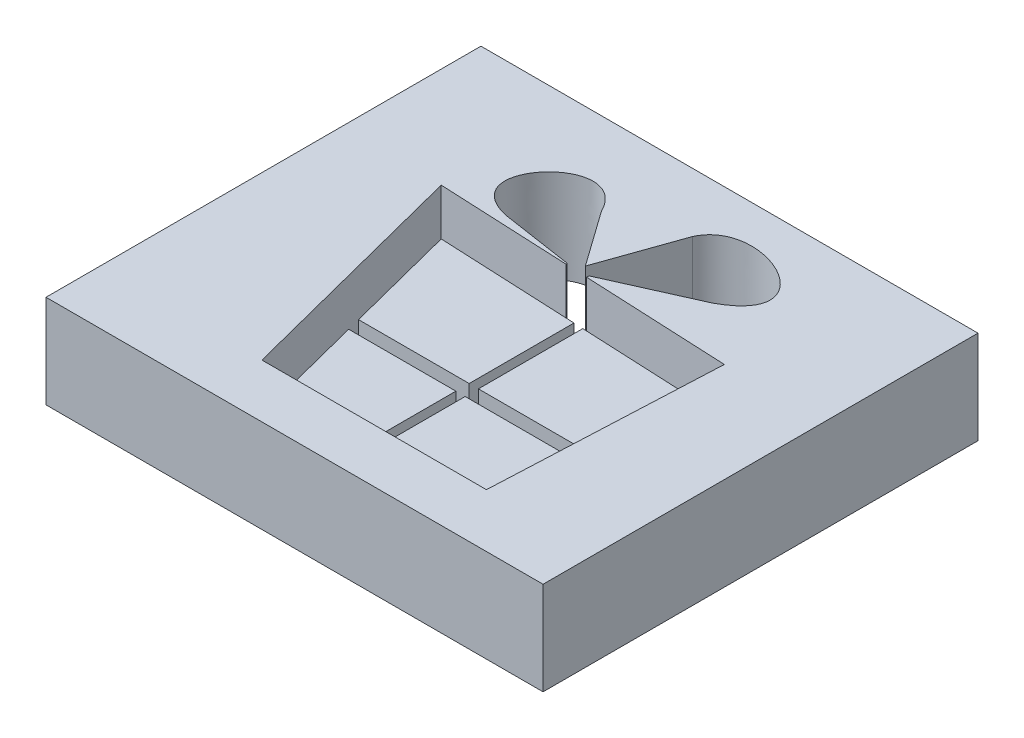
SolidWorks part; units mm, degrees
ref_plane "Front Plane" through (0, 0, 0) normal (0, 0, 1) x (1, 0, 0)
ref_plane "Top Plane" through (0, 0, 0) normal (0, 1, 0) x (1, 0, 0)
ref_plane "Right Plane" through (0, 0, 0) normal (1, 0, 0) x (0, 0, -1)
sketch "Sketch1" plane through (0, 0, 0) normal (0, 1, 0) x (1, 0, 0)
  line L1 (-42.8025, 22.3185) -> (-26.8025, 22.3185)
  line L2 (-42.8025, 22.3185) -> (-42.8025, 8.3185)
  line L3 (-42.8025, 8.3185) -> (-26.8025, 8.3185)
  line L4 (-26.8025, 22.3185) -> (-26.8025, 8.3185)
  dimension "D1" = 16
  dimension "D2" = 14
extrude "Boss-Extrude1" add sketch "Sketch1" along normal blind 3
sketch "Sketch2" plane through (0, 3, 0) normal (0, 1, 0) x (1, 0, 0)
  line L0 (-39.5675, 17.8055) -> (-35.0877, 17.598)
  line L1 (-30.0115, 17.3629) -> (-30.3506, 10.0431)
  line L2 (-30.3506, 10.0431) -> (-37.5756, 10.0431)
  line L3 (-37.5756, 10.0431) -> (-39.5675, 17.8055)
  line L4 (-35.0877, 17.598) -> (-35.0877, 14.2249)
  line L5 (-35.0877, 14.2249) -> (-38.6487, 14.2249)
  line L7 (-38.5391, 13.7977) -> (-35.0883, 13.7977)
  line L8 (-35.0883, 13.7977) -> (-35.0883, 10.0431)
  line L10 (-34.7895, 10.0431) -> (-34.7895, 13.7977)
  line L11 (-34.7895, 13.7977) -> (-30.1767, 13.7977)
  line L13 (-30.1569, 14.2249) -> (-34.7895, 14.2249)
  line L14 (-34.7895, 14.2249) -> (-34.7895, 17.5842)
  line L19 (-34.0907, 20.4179) -> (-34.9919, 17.869)
  line L20 (-36.2576, 19.6502) -> (-34.9919, 17.869)
  line L21 (-37.6692, 18.0034) -> (-35.3618, 17.6542)
  line L22 (-35.3618, 17.6542) -> (-35.3618, 17.6107)
  line L23 (-31.9114, 18.8834) -> (-34.6581, 17.6542)
  line L24 (-34.6581, 17.6542) -> (-34.6581, 17.5781)
  line L25 (-34.7895, 17.5842) -> (-30.0115, 17.3629)
  spline S0 degree 3 poles (-31.9114, 18.8834) (-29.3743, 20.2485) (-33.3059, 22.1353) (-34.0907, 20.4179) knots 0 0 0 0 1 1 1 1
  spline S1 degree 3 poles (-36.2576, 19.6502) (-37.3045, 21.7599) (-40.1557, 18.5404) (-37.6692, 18.0034) knots 0 0 0 0 1 1 1 1
extrude "Cut-Extrude5" cut sketch "Sketch2" against normal blind 3 contours L20 S1 L21 L22 L0 L4 L5 L3 L7 L8 L2 L10 L11 L1 L13 L14 L25 L24 L23 S0 L19
sketch "Sketch3" plane through (0, 3, 0) normal (0, 1, 0) x (1, 0, 0)
  line L0 (-35.0877, 17.598) -> (-39.5675, 17.8055)
  line L1 (-39.5675, 17.8055) -> (-37.5756, 10.0431)
  line L2 (-37.5756, 10.0431) -> (-30.3506, 10.0431)
  line L3 (-30.3506, 10.0431) -> (-30.0115, 17.3629)
  line L4 (-30.0115, 17.3629) -> (-35.0877, 17.598)
extrude "Cut-Extrude6" cut sketch "Sketch3" against normal blind 1.5
